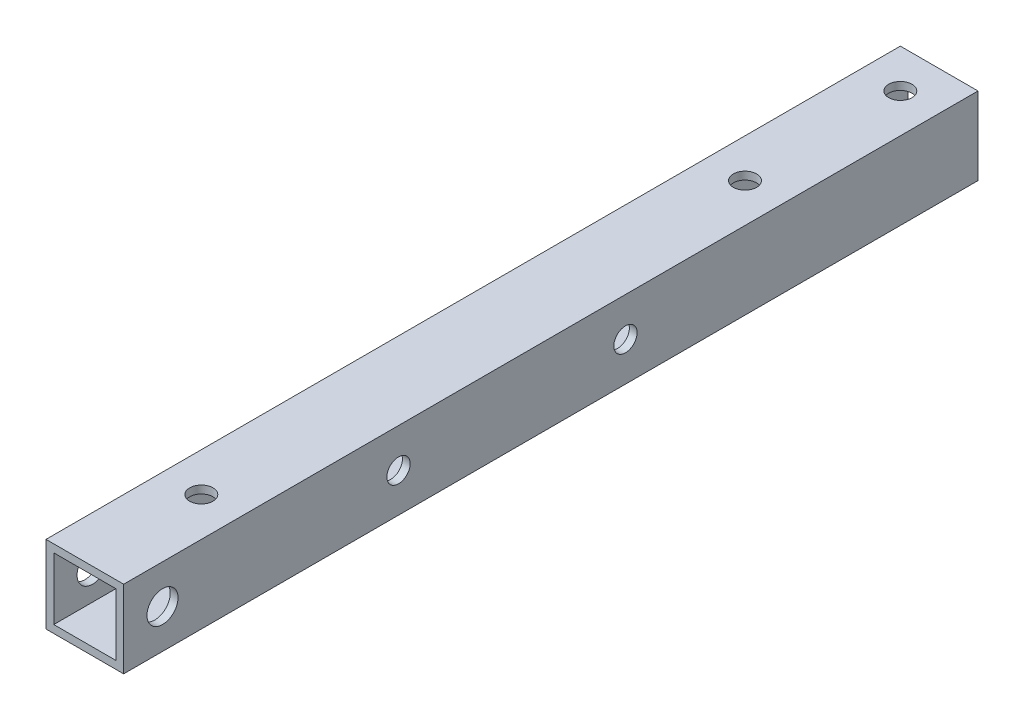
SolidWorks part; units mm, degrees
material "1060 合金"
ref_plane "正面" through (0, 0, 0) normal (0, 0, 1) x (1, 0, 0)
ref_plane "平面" through (0, 0, 0) normal (0, 1, 0) x (1, 0, 0)
ref_plane "右側面" through (0, 0, 0) normal (1, 0, 0) x (0, 0, -1)
sketch "ｽｹｯﾁ1" plane through (0, 0, 0) normal (0, 0, 1) x (1, 0, 0)
  line L1 (5, 5) -> (-5, 5)
  line L2 (5, 5) -> (5, -5)
  line L3 (5, -5) -> (-5, -5)
  line L4 (-5, 5) -> (-5, -5)
  line L5 (5, 5) -> (-5, -5) construction
  line L6 (5, -5) -> (-5, 5) construction
  point P0 (0, 0)
  dimension "D1" = 10
  dimension "D2" = 10
extrude "押し出し-薄板1" add sketch "ｽｹｯﾁ1" along normal blind 100 thin thin type one direction reverse wall 1
sketch "ｽｹｯﾁ3" plane through (0, -5, 0) normal (0, -1, 0) x (1, 0, 0)
  line L0 (0, 100) -> (0, 0) construction
  line L1 (-5, 100) -> (5, 100) construction
  line L2 (-5, 50) -> (5, 50) construction
  line L3 (-5, 100) -> (-5, 0) construction
  line L4 (5, 100) -> (5, 0) construction
  circle A2 centre (0, 15) radius 1.5
  circle A3 centre (0, 85) radius 1.5
  dimension "D1" = 70
  dimension "D4" = 3
extrude "ｶｯﾄ - 押し出し2" cut sketch "ｽｹｯﾁ3" against normal through all
sketch "ｽｹｯﾁ4" plane through (5, 0, 0) normal (1, 0, 0) x (0, 0, -1)
  line L0 (-100, 0) -> (0, 0) construction
  line L1 (-100, -5) -> (-100, 5) construction
  line L3 (-50, -5) -> (-50, 5) construction
  line L4 (-100, -5) -> (0, -5) construction
  line L5 (-100, 5) -> (0, 5) construction
  circle A6 centre (-64.61, 0) radius 1.5
  circle A7 centre (-35.39, 0) radius 1.5
  circle A11 centre (-95, 0) radius 2
  dimension "D1" = 3
  dimension "D2" = 29.22
  dimension "D3" = 5
  dimension "D4" = 4
extrude "ｶｯﾄ - 押し出し3" cut sketch "ｽｹｯﾁ4" against normal through all
sketch "ｽｹｯﾁ5" plane through (0, 0, 0) normal (0, 0, -1) x (-1, 0, 0)
  line L1 (-5, -5) -> (5, -5)
  line L2 (-5, -5) -> (-5, 5)
  line L3 (-5, 5) -> (5, 5)
  line L4 (5, -5) -> (5, 5)
  line L5 (-5, -5) -> (5, 5) construction
  line L6 (-5, 5) -> (5, -5) construction
  point P0 (0, 0)
extrude "押し出し-薄板2" add sketch "ｽｹｯﾁ5" along normal blind 10 thin thin type one direction reverse wall 1
sketch "ｽｹｯﾁ6" plane through (0, 5, 0) normal (0, 1, 0) x (1, 0, 0)
  line L0 (0, 10) -> (0, -100) construction
  line L1 (-5, 10) -> (5, 10) construction
  line L2 (5, -100) -> (-5, -100) construction
  circle A0 centre (0, 5) radius 1.5
  dimension "D1" = 5
  dimension "D2" = 3
extrude "ｶｯﾄ - 押し出し4" cut sketch "ｽｹｯﾁ6" against normal through all
